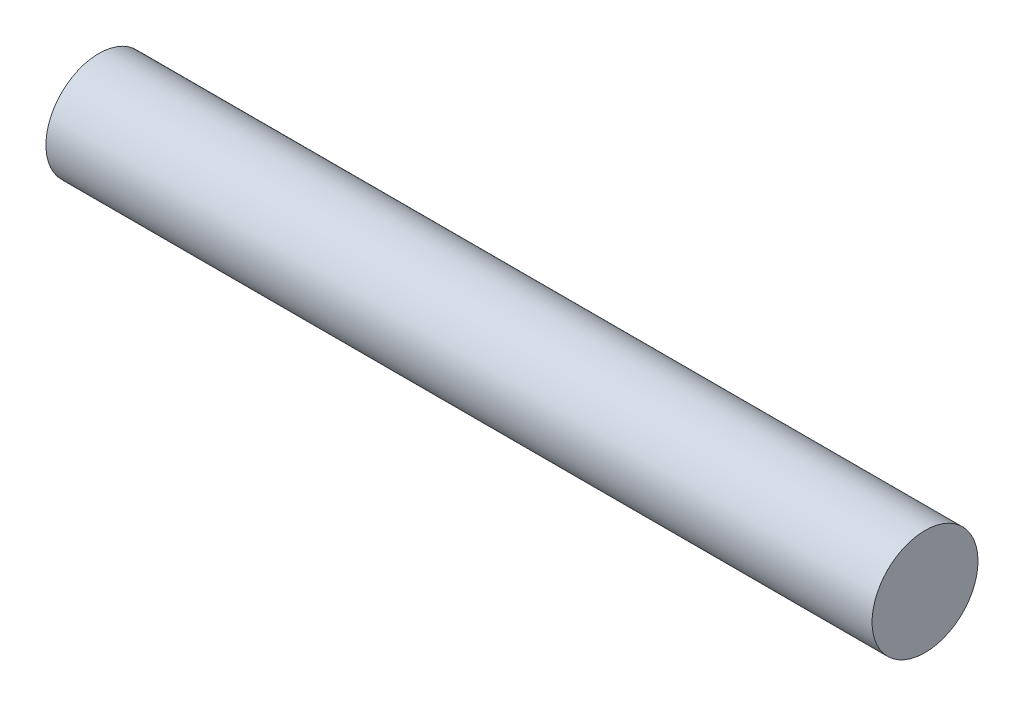
SolidWorks part; units mm, degrees
ref_plane "Front Plane" through (0, 0, 0) normal (0, 0, 1) x (1, 0, 0)
ref_plane "Top Plane" through (0, 0, 0) normal (0, 1, 0) x (1, 0, 0)
ref_plane "Right Plane" through (0, 0, 0) normal (1, 0, 0) x (0, 0, -1)
sketch "Sketch1" plane through (0, 0, 0) normal (1, 0, 0) x (0, 0, -1)
  circle A0 centre (0, 0) radius 12.7
  dimension "D1" = 25.4
extrude "Boss-Extrude1" add sketch "Sketch1" along normal blind 198.12
